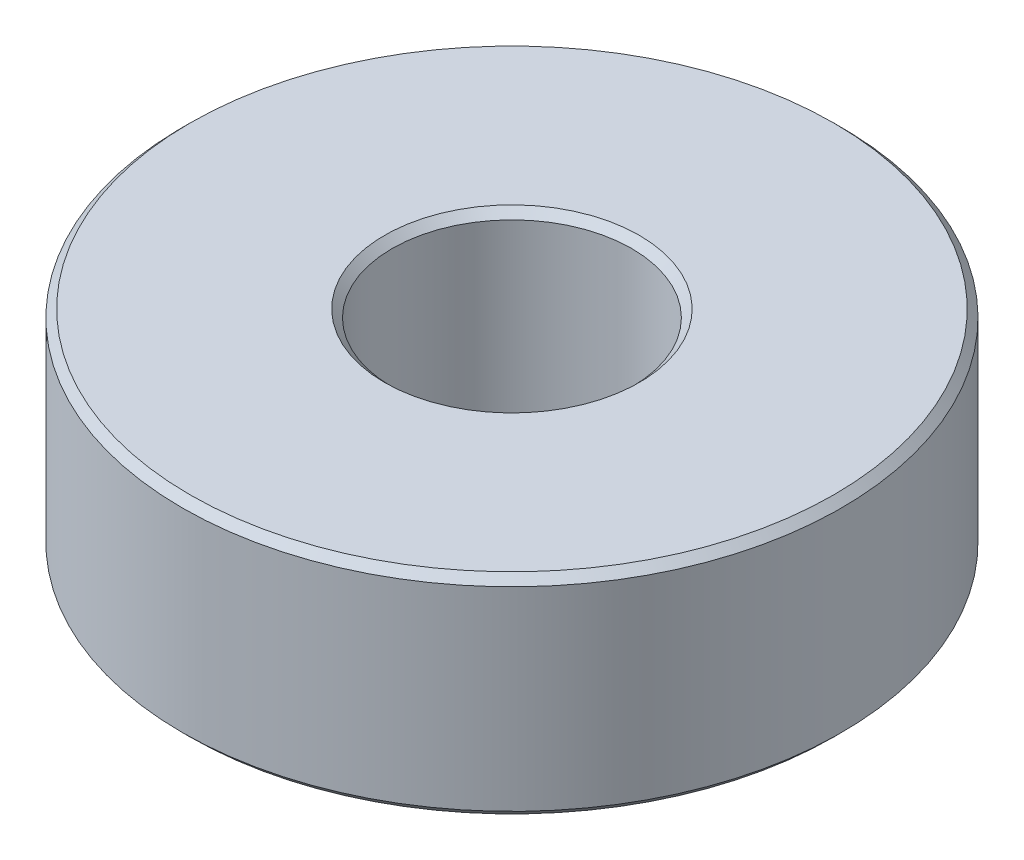
SolidWorks part; units mm, degrees
ref_plane "Front Plane" through (0, 0, 0) normal (0, 0, 1) x (1, 0, 0)
ref_plane "Top Plane" through (0, 0, 0) normal (0, 1, 0) x (1, 0, 0)
ref_plane "Right Plane" through (0, 0, 0) normal (1, 0, 0) x (0, 0, -1)
sketch "Sketch1" plane through (0, 0, 0) normal (0, 1, 0) x (1, 0, 0)
  circle A0 centre (0, 0) radius 4
  circle A1 centre (0, 0) radius 11
  dimension "D1" = 22
  dimension "D2" = 8
extrude "Boss-Extrude1" add sketch "Sketch1" along normal blind 7
chamfer "Chamfer1" distance 0.254 angle 45 4 edges at (0, 0, 4) (0, 0, 11) (0, 7, 4) (0, 7, 11)
